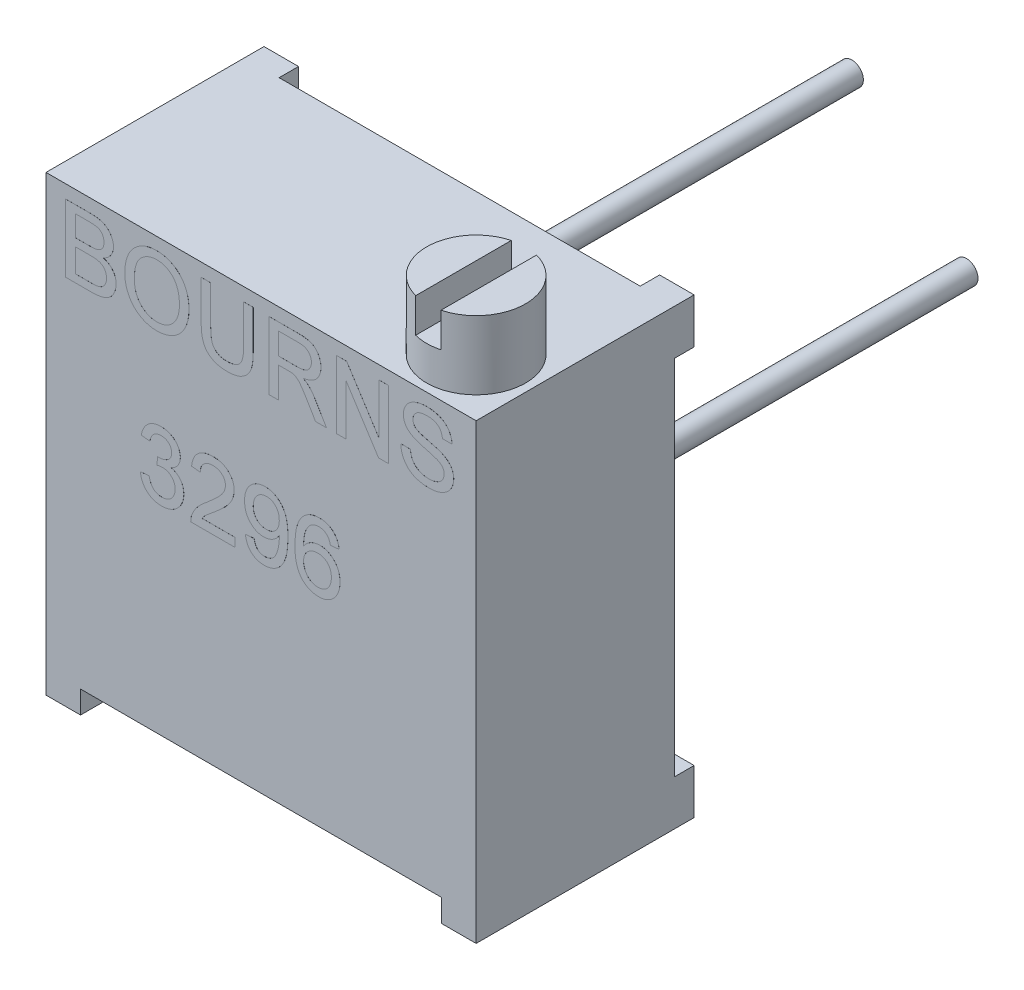
SolidWorks part; units mm, degrees
ref_plane "Plane1" through (0, 0, 0) normal (0, 0, 1) x (1, 0, 0)
ref_plane "Plane2" through (0, 0, 0) normal (0, 1, 0) x (1, 0, 0)
ref_plane "Plane3" through (0, 0, 0) normal (1, 0, 0) x (0, 0, -1)
sketch "Sketch1" plane through (0, 0, 0) normal (0, 0, 1) x (1, 0, 0)
  line L1 (-4.765, 0) -> (4.765, 0)
  line L2 (-4.765, 0) -> (-4.765, 10.03)
  line L3 (-4.765, 10.03) -> (4.765, 10.03)
  line L4 (4.765, 0) -> (4.765, 10.03)
  dimension "D1" = 9.53
  dimension "D2" = 10.03
extrude "Extrude1" add sketch "Sketch1" along normal blind 4.4
sketch "Sketch2" plane through (0, 0, 4.4) normal (0, 0, 1) x (1, 0, 0)
  line L0 (-4.765, 0) -> (4.765, 0) construction
  line L1 (-4, 0) -> (4, 0)
  line L2 (-4, 0) -> (-4, 0.5)
  line L3 (-4, 0.5) -> (4, 0.5)
  line L4 (4, 0) -> (4, 0.5)
  dimension "D1" = 8
  dimension "D2" = 0.5
extrude "Cut-Extrude1" cut sketch "Sketch2" against normal through all
sketch "Sketch3" plane through (0, 0, 0) normal (0, 0, -1) x (-1, 0, 0)
  line L1 (-4.765, 0) -> (-4, 0)
  line L2 (-4.765, 0) -> (-4.765, 1)
  line L3 (-4.765, 1) -> (-4, 1)
  line L4 (-4, 0) -> (-4, 1)
  line L5 (4.765, 0) -> (4, 0)
  line L6 (4.765, 0) -> (4.765, 1)
  line L7 (4.765, 1) -> (4, 1)
  line L8 (4, 0) -> (4, 1)
  line L9 (4.765, 10.03) -> (4, 10.03)
  line L10 (4.765, 10.03) -> (4.765, 9.03)
  line L11 (4.765, 9.03) -> (4, 9.03)
  line L12 (4, 10.03) -> (4, 9.03)
  line L13 (-4.765, 10.03) -> (-4, 10.03)
  line L14 (-4.765, 10.03) -> (-4.765, 9.03)
  line L15 (-4.765, 9.03) -> (-4, 9.03)
  line L16 (-4, 10.03) -> (-4, 9.03)
  dimension "D1" = 1
  dimension "D2" = 1
extrude "Extrude2" add sketch "Sketch3" along normal blind 0.43
sketch "Sketch4" plane through (0, 0.5, 0) normal (0, -1, 0) x (1, 0, 0)
  line L0 (0, 0) -> (0, 1.98) construction
  line L1 (-2.54, 1.98) -> (2.54, 1.98) construction
  line L2 (4.765, -0.43) -> (4, -0.43) construction
  circle A0 centre (2.54, 1.98) radius 0.255
  circle A1 centre (0, 1.98) radius 0.255
  circle A2 centre (-2.54, 1.98) radius 0.255
  dimension "D4" = 0.51
  dimension "D1" = 2.41
  dimension "D2" = 2.54
  dimension "D3" = 2.54
sketch "Sketch5" plane through (0, 10.03, 0) normal (0, 1, 0) x (-1, 0, 0)
  line L0 (-4.765, 4.4) -> (4.765, 4.4) construction
  line L1 (-4.765, 4.4) -> (-4.765, -0.43) construction
  circle A0 centre (-3.495, 3.13) radius 1.095
  dimension "D3" = 2.19
  dimension "D1" = 1.27
  dimension "D2" = 1.27
extrude "Extrude4" add sketch "Sketch5" along normal blind 1.52
sketch "Sketch6" plane through (0, 11.55, 0) normal (0, 1, 0) x (-1, 0, 0)
  line L0 (-3.495, 3.13) -> (-3.495, 1.593) construction
  line L1 (-3.215, 1.593) -> (-3.775, 1.593)
  line L2 (-3.215, 1.593) -> (-3.215, 4.7702)
  line L3 (-3.215, 4.7702) -> (-3.775, 4.7702)
  line L4 (-3.775, 1.593) -> (-3.775, 4.7702)
  dimension "D1" = 0.56
extrude "Cut-Extrude2" cut sketch "Sketch6" against normal blind 0.76
sketch "Sketch7" plane through (0, 0, 4.4) normal (0, 0, 1) x (1, 0, 0)
  text T0 "BOURNS\r\n   3296" font "Arial" height 1.5
extrude "Extrude5" add sketch "Sketch7" along normal blind 0.001
sketch "Sketch8" plane through (0, 0, 0) normal (0, 0, -1) x (-1, 0, 0)
  line L0 (0, 0) -> (0, 7.77) construction
  line L1 (0, 5.23) -> (-2.54, 5.23) construction
  line L2 (0, 5.23) -> (2.54, 5.23) construction
  circle A0 centre (-2.54, 5.23) radius 0.255
  circle A1 centre (0, 7.77) radius 0.255
  circle A2 centre (2.54, 5.23) radius 0.255
  dimension "D5" = 0.51
  dimension "D1" = 5.23
  dimension "D2" = 2.54
  dimension "D3" = 2.54
  dimension "D4" = 2.54
extrude "Extrude6" add sketch "Sketch8" along normal blind 8.69
